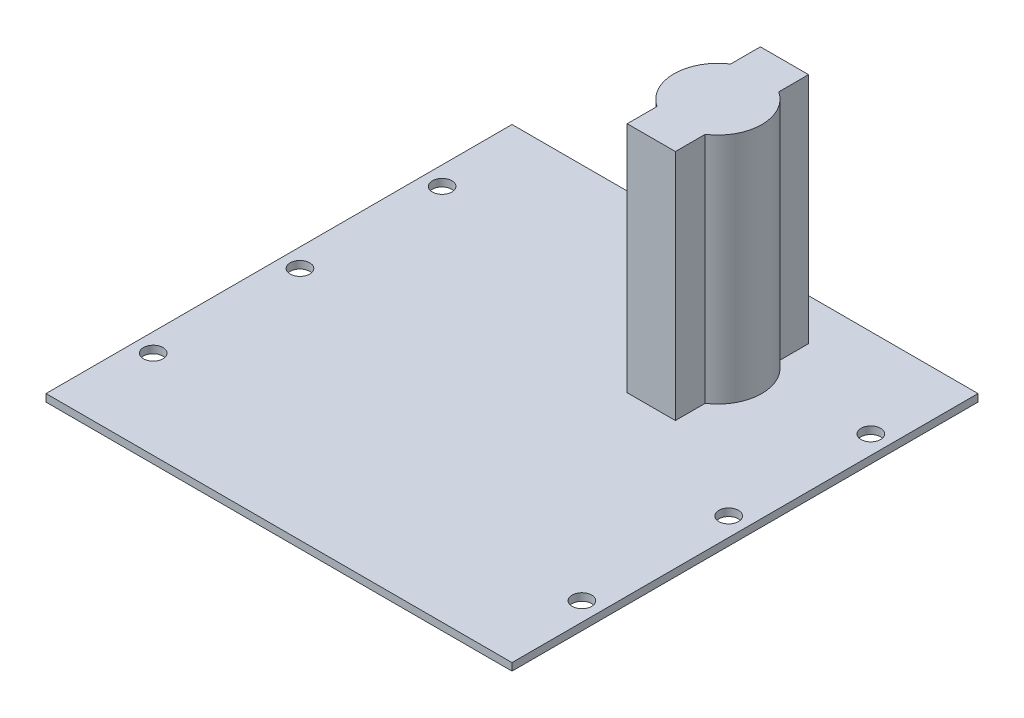
SolidWorks part; units mm, degrees
ref_plane "Alzado" through (0, 0, 0) normal (0, 0, 1) x (1, 0, 0)
ref_plane "Planta" through (0, 0, 0) normal (0, 1, 0) x (1, 0, 0)
ref_plane "Vista lateral" through (0, 0, 0) normal (1, 0, 0) x (0, 0, -1)
sketch "Croquis1" plane through (0, 0, 0) normal (0, 1, 0) x (1, 0, 0)
  line L0 (0, 0) -> (0, 37.1864) construction
  line L1 (-50, -50) -> (50, -50)
  line L2 (-50, -50) -> (-50, 50)
  line L3 (-50, 50) -> (50, 50)
  line L4 (50, -50) -> (50, 50)
  line L5 (-50, -50) -> (50, 50) construction
  line L6 (-50, 50) -> (50, -50) construction
  circle A0 centre (-46, 31) radius 2.1
  circle A1 centre (-46, 0.5) radius 2.1
  circle A2 centre (-46, -31) radius 2.1
  circle A3 centre (46, -31) radius 2.1
  circle A4 centre (46, 0.5) radius 2.1
  circle A5 centre (46, 31) radius 2.1
  point P0 (0, 0)
  dimension "D3" = 19
  dimension "D4" = 30.5
  dimension "D5" = 19
  dimension "D6" = 31.5
  dimension "D7" = 4.2
  dimension "D8" = 4
  dimension "D1" = 100
  dimension "D2" = 100
extrude "Saliente-Extruir1" add sketch "Croquis1" along normal blind 1.6
sketch "Croquis2" plane through (0, 1.6, 0) normal (0, 1, 0) x (1, 0, 0)
  line L1 (12.2174, 41.0845) -> (22.5539, 41.0845)
  line L2 (12.2174, 41.0845) -> (12.2174, 12.5075)
  line L3 (12.2174, 12.5075) -> (22.5539, 12.5075)
  line L4 (22.5539, 41.0845) -> (22.5539, 12.5075)
  line L5 (12.2174, 41.0845) -> (22.5539, 12.5075) construction
  line L6 (12.2174, 12.5075) -> (22.5539, 41.0845) construction
  circle A0 centre (17.3857, 26.796) radius 9.4345
  point P0 (17.3857, 26.796)
extrude "Saliente-Extruir2" add sketch "Croquis2" along normal blind 50 contours L2 A0 | L4 A0 L2 | A0 L4 L1 L2 | L4 A0 | A0 L2 L3 L4
